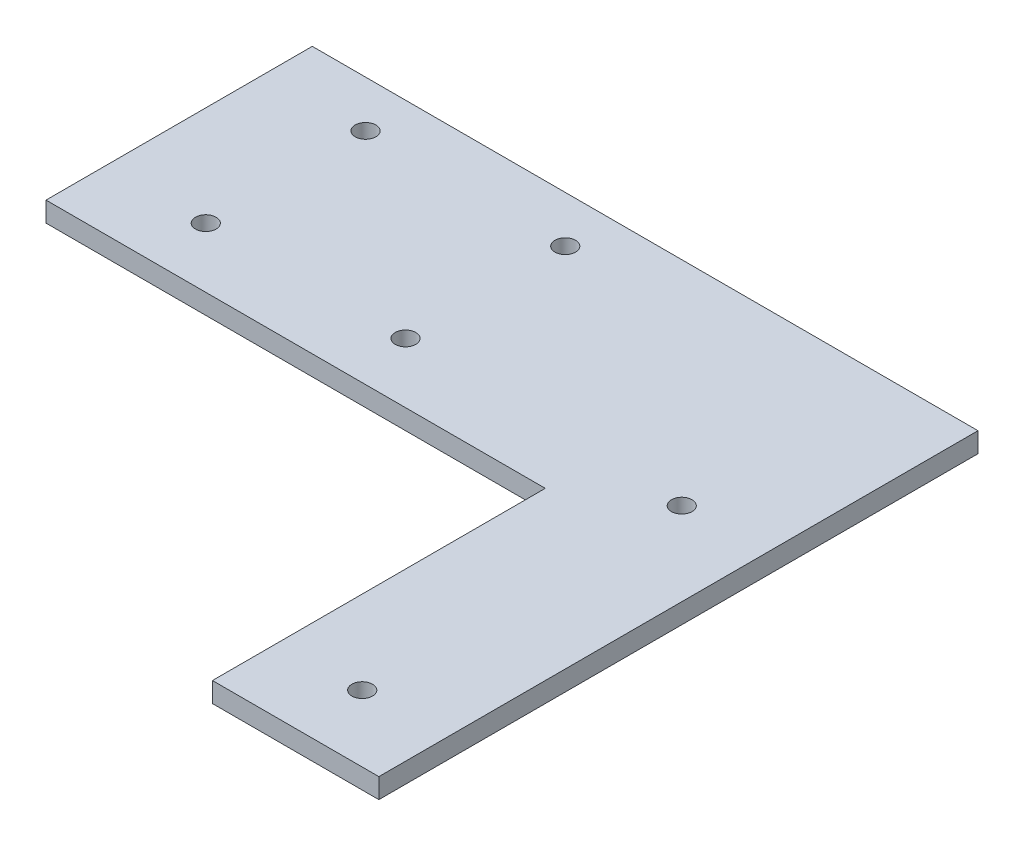
SolidWorks part; units mm, degrees
material "6061 合金"
ref_plane "前视基准面" through (0, 0, 0) normal (0, 0, 1) x (1, 0, 0)
ref_plane "上视基准面" through (0, 0, 0) normal (0, 1, 0) x (1, 0, 0)
ref_plane "右视基准面" through (0, 0, 0) normal (1, 0, 0) x (0, 0, -1)
sketch "草图1" plane through (0, 0, 0) normal (0, 1, 0) x (1, 0, 0)
  line L1 (-50, 45) -> (50, 45)
  line L2 (-50, 45) -> (-50, -45)
  line L3 (-50, -45) -> (50, -45)
  line L4 (50, 45) -> (50, -45)
  line L5 (-50, 45) -> (50, -45) construction
  line L6 (-50, -45) -> (50, 45) construction
  line L7 (-50, -45) -> (25, -45)
  line L8 (-50, -45) -> (-50, 5)
  line L9 (-50, 5) -> (25, 5)
  line L10 (25, -45) -> (25, 5)
  point P0 (0, 0)
  dimension "D1" = 90
  dimension "D2" = 100
  dimension "D3" = 75
  dimension "D4" = 50
extrude "凸台-拉伸1" add sketch "草图1" along normal blind 3 contours L10 L3 L4 L1 L2 L9
ref_plane "基准面1" through (0, 0, 0) normal (0, -1, 0) x (-1, 0, 0)
sketch "草图2" plane through (0, 0, 0) normal (0, -1, 0) x (-1, 0, 0)
  circle A0 centre (5, 38) radius 1.55
  circle A1 centre (5, 14) radius 1.55
  circle A2 centre (35, 38) radius 1.55
  circle A3 centre (35, 14) radius 1.55
extrude "切除-拉伸1" cut sketch "草图2" against normal blind 10
ref_plane "基准面2" through (0, 0, 0) normal (0, -1, 0) x (-1, 0, 0)
sketch "草图3" plane through (0, 0, 0) normal (0, -1, 0) x (-1, 0, 0)
  circle A0 centre (-37.5, 13) radius 1.55
  circle A1 centre (-37.5, -35) radius 1.55
extrude "切除-拉伸2" cut sketch "草图3" against normal blind 10
